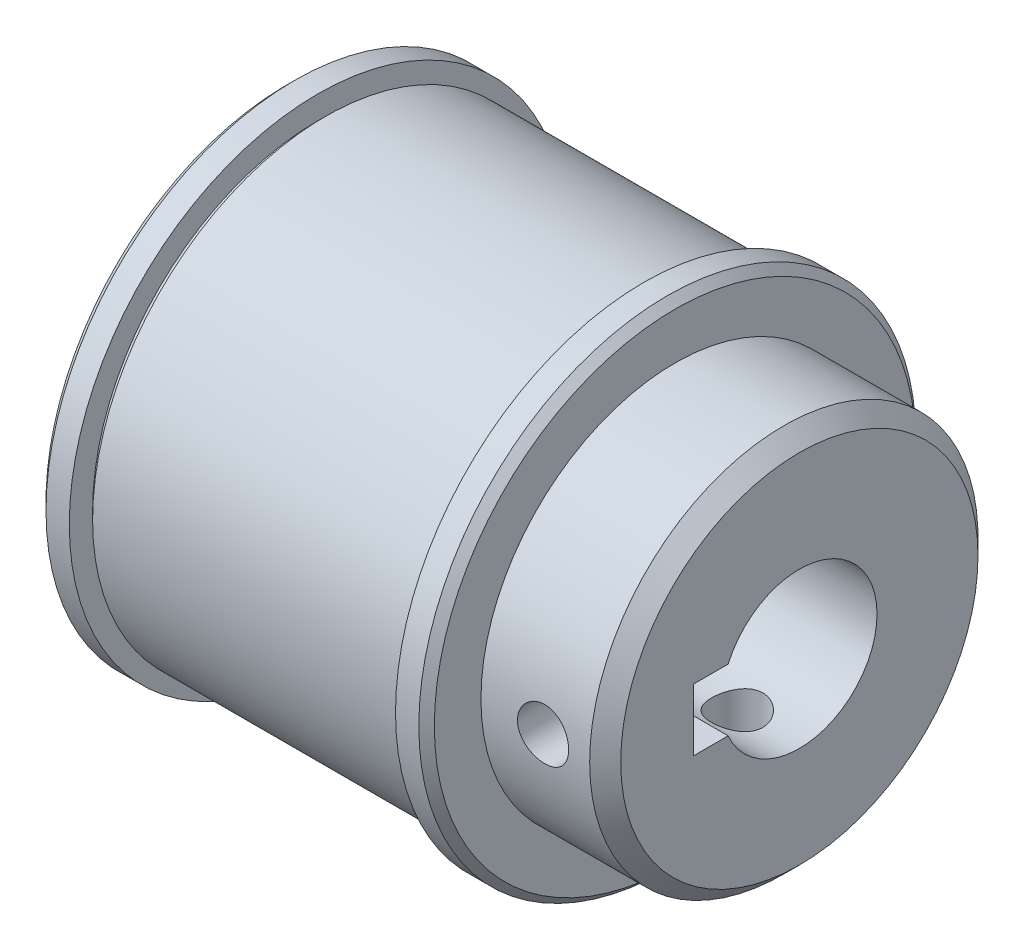
SolidWorks part; units mm, degrees
ref_plane "Front" through (0, 0, 0) normal (0, 0, 1) x (1, 0, 0)
ref_plane "Top" through (0, 0, 0) normal (0, 1, 0) x (1, 0, 0)
ref_plane "Right" through (0, 0, 0) normal (1, 0, 0) x (0, 0, -1)
sketch "Sketch1" plane through (0, 0, 0) normal (0, 0, 1) x (1, 0, 0)
  line L0 (-28.0532, 0) -> (45.1747, 0) construction
  line L1 (0, 0) -> (0, 16)
  line L2 (0, 16) -> (2, 16)
  line L3 (2, 16) -> (2, 14.5)
  line L4 (2.5, 15) -> (22.5, 15)
  line L5 (23, 14.5) -> (23, 16)
  line L6 (23, 16) -> (25, 16)
  line L7 (25, 16) -> (25, 12.5)
  line L8 (25, 12.5) -> (33, 12.5)
  line L9 (33, 12.5) -> (33, 0)
  line L10 (0, 0) -> (33, 0)
  line L12 (2, 14.5) -> (2.5, 14.5)
  line L13 (2.5, 14.5) -> (2.5, 15)
  line L14 (22.5, 15) -> (22.5, 14.5)
  line L15 (22.5, 14.5) -> (23, 14.5)
  dimension "D1" = 33
  dimension "D2" = 25
  dimension "D3" = 32
  dimension "D4" = 30
  dimension "D5" = 2
  dimension "D6" = 23
  dimension "D7" = 25
  dimension "D8" = 29
  dimension "D9" = 0.5
  dimension "D10" = 0.5
revolve "Revolve1" add sketch "Sketch1" angle 360 about L0
sketch "Sketch2" plane through (0, 0, 0) normal (0, 0, 1) x (1, 0, 0)
  line L0 (-6.4918, 0) -> (37.0459, 0) construction
  line L1 (33, -12.5) -> (33, 12.5) construction
  line L2 (0, 0) -> (33, 0)
  line L3 (0, 0) -> (0, 5)
  line L4 (0, 5) -> (33, 5)
  line L5 (33, 0) -> (33, 5)
  dimension "D1" = 10
revolve "Cut-Revolve1" cut sketch "Sketch2" angle 360 about L0
sketch "Sketch3" plane through (33, 0, 0) normal (1, 0, 0) x (0, 0, -1)
  line L0 (-17.9548, 0) -> (19.7275, 0) construction
  line L2 (-6.8, 2) -> (-4.5826, 2)
  line L3 (-6.8, 2) -> (-6.8, -2)
  line L4 (-6.8, -2) -> (-4.5826, -2)
  line L5 (-4.5826, 2) -> (-4.5826, -2)
  circle A0 centre (0, 0) radius 5 construction
  dimension "D1" = 4
  dimension "D2" = 1.8
extrude "Cut-Extrude1" cut sketch "Sketch3" against normal through all
ref_plane "Plane1" through (0, 0, 12.5) normal (0, 0, 1) x (1, 0, 0)
hole_wizard "M4x0.7 Tapped Hole1" positions "Sketch5" profile "Sketch4" tap size "M4x0.7" standard "JIS"
sketch "Sketch5" plane through (0, 0, 12.5) normal (0, 0, 1) x (1, 0, 0)
  line L0 (0, 16) -> (0, -16) construction
  point P2 (29, 0)
  dimension "D1" = 29
sketch "Sketch4" plane through (29, 0, 12.5) normal (1, 0, 0) x (0, -1, 0)
  line L0 (0, 0) -> (0, 25)
  line L1 (0, 25) -> (1.65, 25)
  line L2 (1.65, 25) -> (1.65, 0)
  line L5 (1.65, 0) -> (0, 0)
  line L11 (0, -6.35) -> (0, 107.95) construction
  dimension "Thru Tap Drill Dia." = 3.3
  dimension "Thru Tap Drill Depth" = 25
cosmetic thread "Hole Thread1" parameters "D2"=4
pattern_circular "CirPattern1" count 2 over 90 about axis through (-6.4918, 0, 0) along (-1, 0, 0) of "M4x0.7 Tapped Hole1"
chamfer "Chamfer1" distance 1 angle 45 1 edges at (33, 0, 12.5)
chamfer "Chamfer2" distance 0.5 angle 45 2 edges at (0, 0, 16) (25, 0, 16)
